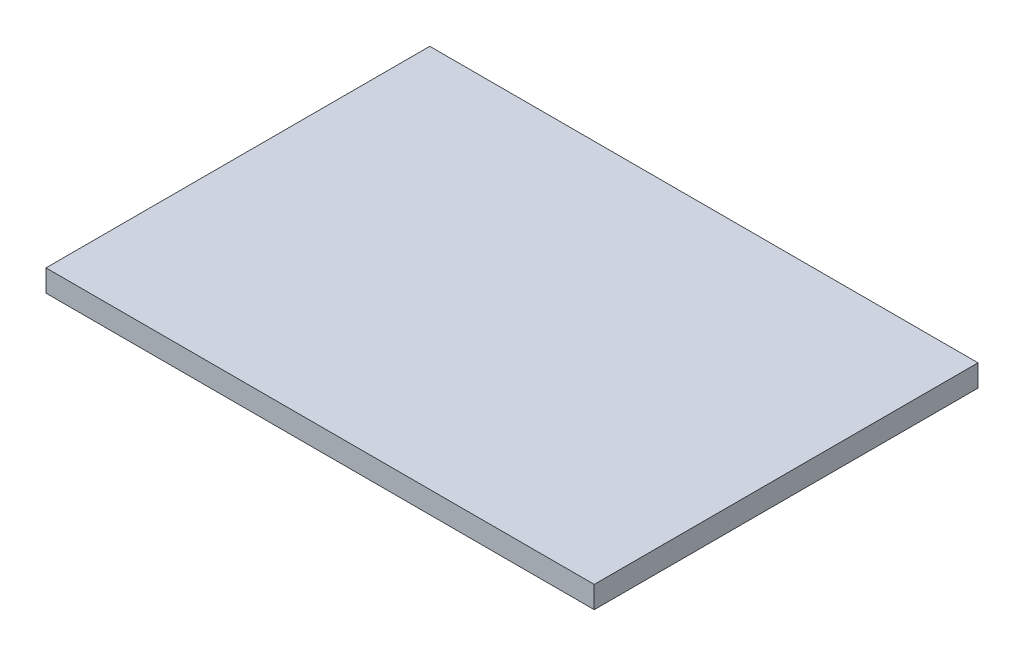
SolidWorks part; units mm, degrees
ref_plane "Front Plane" through (0, 0, 0) normal (0, 0, 1) x (1, 0, 0)
ref_plane "Top Plane" through (0, 0, 0) normal (0, 1, 0) x (1, 0, 0)
ref_plane "Right Plane" through (0, 0, 0) normal (1, 0, 0) x (0, 0, -1)
sketch "Sketch1" plane through (0, 0, 0) normal (0, 1, 0) x (1, 0, 0)
  line L1 (-250, 175) -> (250, 175)
  line L2 (-250, 175) -> (-250, -175)
  line L3 (-250, -175) -> (250, -175)
  line L4 (250, 175) -> (250, -175)
  line L5 (-250, 175) -> (250, -175) construction
  line L6 (-250, -175) -> (250, 175) construction
  point P0 (0, 0)
  dimension "D1" = 350
  dimension "D2" = 500
extrude "Boss-Extrude1" add sketch "Sketch1" along normal blind 20
